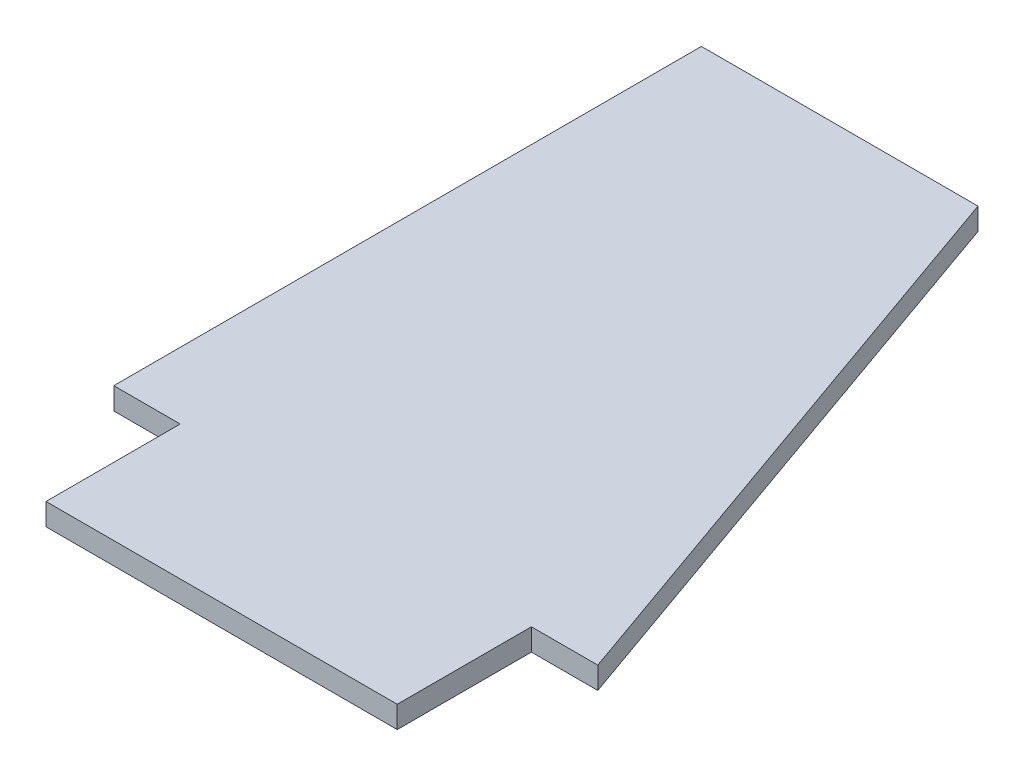
SolidWorks part; units mm, degrees
ref_plane "Front Plane" through (0, 0, 0) normal (0, 0, 1) x (1, 0, 0)
ref_plane "Top Plane" through (0, 0, 0) normal (0, 1, 0) x (1, 0, 0)
ref_plane "Right Plane" through (0, 0, 0) normal (1, 0, 0) x (0, 0, -1)
sketch "Sketch1" plane through (0, 0, 0) normal (0, 1, 0) x (1, 0, 0)
  line L0 (0, 0) -> (0, 84.9884)
  line L1 (0, 84.9884) -> (40.005, 84.9884)
  line L2 (40.005, 84.9884) -> (70.0024, 0)
  line L3 (70.0024, 0) -> (0, 0)
  line L5 (9.6012, 0) -> (60.4012, 0)
  line L6 (9.6012, 0) -> (9.6012, -19.4056)
  line L7 (9.6012, -19.4056) -> (60.4012, -19.4056)
  line L8 (60.4012, 0) -> (60.4012, -19.4056)
  point P9 (35.0012, 0)
  point P10 (35.0012, -19.4056)
  dimension "D1" = 70.0024
  dimension "D2" = 40.005
  dimension "D3" = 84.9884
  dimension "D4" = 19.4056
  dimension "D5" = 50.8
extrude "Boss-Extrude1" add sketch "Sketch1" along normal blind 3.175 contours L8 L3 L6 L7 | L3 L2 L1 L0
